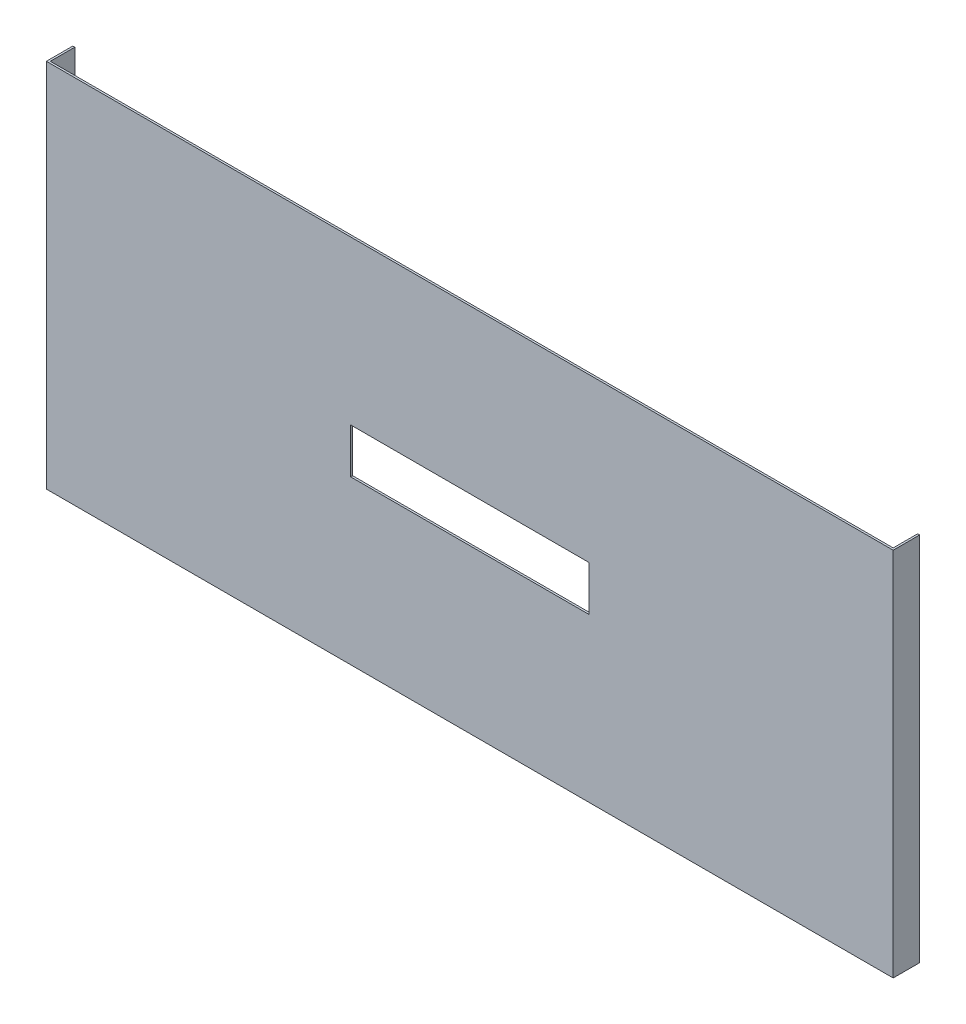
SolidWorks part; units mm, degrees
ref_plane "Front Plane" through (0, 0, 0) normal (0, 0, 1) x (1, 0, 0)
ref_plane "Top Plane" through (0, 0, 0) normal (0, 1, 0) x (1, 0, 0)
ref_plane "Right Plane" through (0, 0, 0) normal (1, 0, 0) x (0, 0, -1)
other "Configuration Table"
sketch "Sketch1" plane through (0, 0, 0) normal (0, 1, 0) x (1, 0, 0)
  line L0 (30, -40) -> (30, -20)
  line L1 (30, -20) -> (31.5, -20)
  line L2 (31.5, -20) -> (31.5, -38.5)
  line L3 (31.5, -38.5) -> (668.5, -38.5)
  line L4 (668.5, -38.5) -> (668.5, -20)
  line L5 (668.5, -20) -> (670, -20)
  line L6 (670, -20) -> (670, -40)
  line L7 (670, -40) -> (30, -40)
extrude "TOPPING_klape_alt1_kapak_1" add sketch "Sketch1" along normal blind 280 from offset 460 separate body
sketch "Sketch2" plane through (0, 0, 0) normal (0, 0, 1) x (1, 0, 0)
  line L1 (260, 583) -> (440, 583)
  line L2 (260, 583) -> (260, 617)
  line L3 (260, 617) -> (440, 617)
  line L4 (440, 583) -> (440, 617)
extrude "TOPPING_klape_alt1_kapak_2" cut sketch "Sketch2" along normal blind 14 from offset 27
